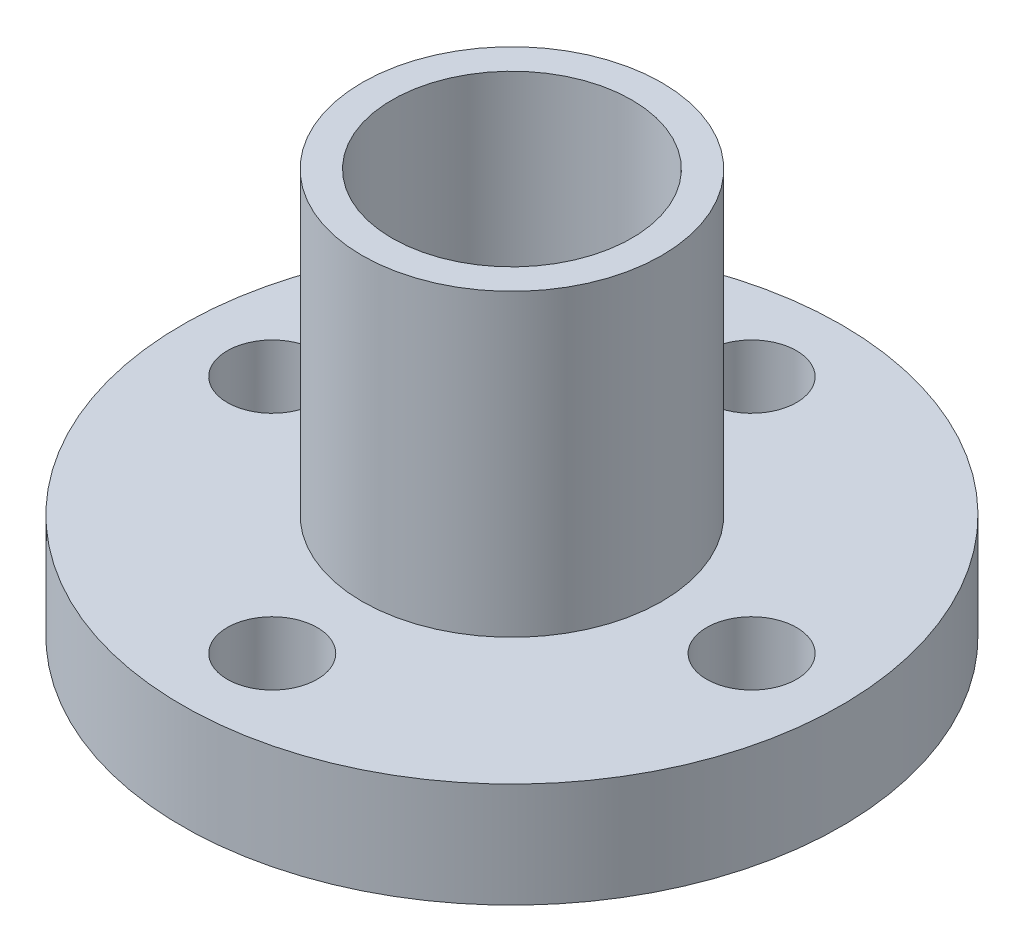
SolidWorks part; units mm, degrees
ref_plane "前视基准面" through (0, 0, 0) normal (0, 0, 1) x (1, 0, 0)
ref_plane "上视基准面" through (0, 0, 0) normal (0, 1, 0) x (1, 0, 0)
ref_plane "右视基准面" through (0, 0, 0) normal (1, 0, 0) x (0, 0, -1)
sketch "草图1" plane through (0, 0, 0) normal (0, 0, 1) x (1, 0, 0)
  line L0 (0, -4.1667) -> (0, 14.1667) construction
  line L1 (4, 0) -> (4, 15.5)
  line L2 (4, 15.5) -> (5, 15.5)
  line L3 (5, 15.5) -> (5, 5.5)
  line L4 (5, 5.5) -> (11, 5.5)
  line L5 (11, 5.5) -> (11, 2)
  line L6 (11, 2) -> (5, 2)
  line L7 (5, 2) -> (5, 0)
  line L8 (5, 0) -> (4, 0)
  dimension "D1" = 8
  dimension "D2" = 1
  dimension "D3" = 22
  dimension "D4" = 3.5
  dimension "D5" = 10
  dimension "D6" = 2
revolve "旋转1" add sketch "草图1" angle 360 about L0
cosmetic thread "装饰螺纹线1" parameters "D1"=5, "D2"=24
sketch "草图2" plane through (0, 5.5, 0) normal (0, 1, 0) x (1, 0, 0)
  circle A0 centre (0, 0) radius 8 construction
  circle A1 centre (0, 8) radius 1.5
  circle A2 centre (8, 0) radius 1.5
  circle A3 centre (0, -8) radius 1.5
  circle A4 centre (-8, 0) radius 1.5
  dimension "D1" = 16
  dimension "D2" = 3
extrude "切除-拉伸1" cut sketch "草图2" against normal through all
